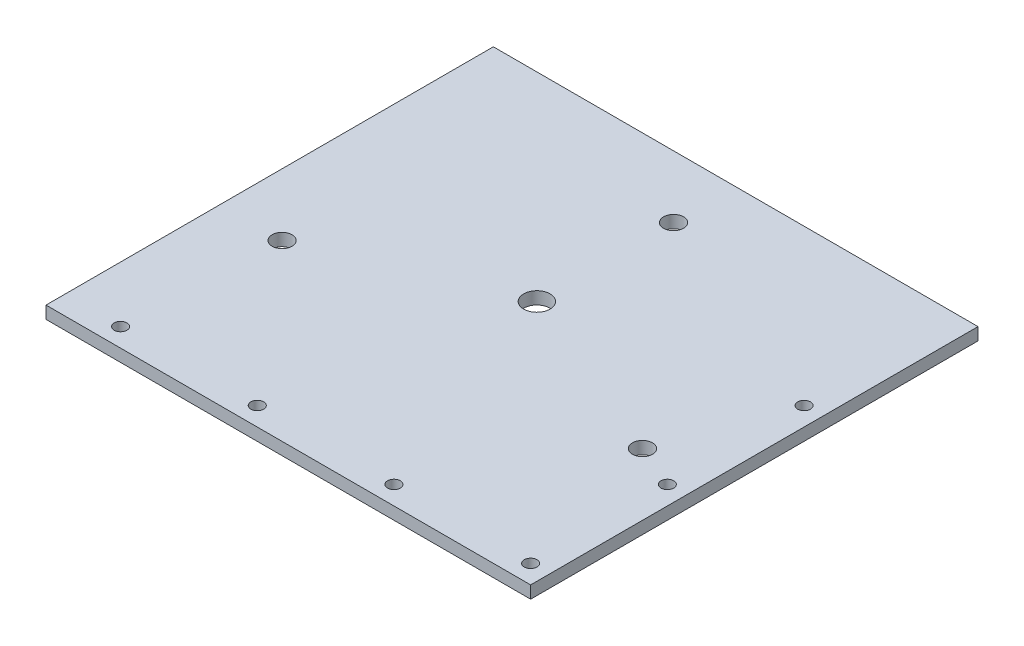
SolidWorks part; units mm, degrees
material "6061 Alloy"
ref_plane "Front Plane" through (0, 0, 0) normal (0, 0, 1) x (1, 0, 0)
ref_plane "Top Plane" through (0, 0, 0) normal (0, 1, 0) x (1, 0, 0)
ref_plane "Right Plane" through (0, 0, 0) normal (1, 0, 0) x (0, 0, -1)
sketch "Sketch1" plane through (0, 0, 0) normal (0, 1, 0) x (1, 0, 0)
  line L1 (-61.9125, -57.15) -> (61.9125, -57.15)
  line L2 (-61.9125, -57.15) -> (-61.9125, 57.15)
  line L3 (-61.9125, 57.15) -> (61.9125, 57.15)
  line L4 (61.9125, -57.15) -> (61.9125, 57.15)
  line L5 (-61.9125, -57.15) -> (61.9125, 57.15) construction
  line L6 (-61.9125, 57.15) -> (61.9125, -57.15) construction
  point P0 (0, 0)
  dimension "D1" = 114.3
  dimension "D2" = 123.825
extrude "Plate" add sketch "Sketch1" along normal blind 3.175 contours L1 L4 L3 L2
hole_wizard "Force Plate Post (1/4\"-20 Clearance Hole)" positions "Sketch21" profile "Sketch20" hole size "1/4" standard "ANSI Inch" end condition up to next
sketch "Sketch21" plane through (0, 3.175, 0) normal (0, 1, 0) x (1, 0, 0)
  point P0 (0, 6.35)
  dimension "D1" = 6.35
sketch "Sketch20" plane through (0, 3.175, -6.35) normal (1, 0, 0) x (0, 0, 1)
  line L0 (0, 0) -> (0, 3.175)
  line L1 (0, 3.175) -> (3.3782, 3.175)
  line L2 (3.3782, 3.175) -> (3.3782, 0)
  line L5 (3.3782, 0) -> (0, 0)
  line L11 (0, -6.35) -> (0, 107.95) construction
  dimension "Thru Hole Dia." = 6.7564
  dimension "Thru Hole Depth" = 3.175
hole_wizard "#4 Clearance Hole1" positions "Sketch23" profile "Sketch22" hole size "#4" standard "ANSI Inch" end condition up to next
sketch "Sketch23" plane through (0, 3.175, 0) normal (0, 1, 0) x (1, 0, 0)
  line L0 (57.15, -57.15) -> (57.15, 57.15) construction
  line L1 (-61.9125, -57.15) -> (61.9125, -57.15) construction
  line L2 (-61.9125, 57.15) -> (61.9125, 57.15) construction
  line L4 (-61.9125, -52.3875) -> (61.9125, -52.3875) construction
  line L5 (-61.9125, -57.15) -> (-61.9125, 57.15) construction
  line L6 (61.9125, -57.15) -> (61.9125, 57.15) construction
  point P17 (57.15, -52.3875)
  point P19 (57.15, -17.4625)
  point P21 (57.15, 17.4625)
  point P25 (22.225, -52.3875)
  point P27 (-12.7, -52.3875)
  point P35 (-47.625, -52.3875)
  dimension "D1" = 4.7625
  dimension "D2" = 4.7625
  dimension "D3" = 34.925
  dimension "D4" = 34.925
  dimension "D5" = 34.925
  dimension "D6" = 34.925
  dimension "D7" = 34.925
sketch "Sketch22" plane through (57.15, 3.175, 52.3875) normal (1, 0, 0) x (0, 0, 1)
  line L0 (0, 0) -> (0, 3.175)
  line L1 (0, 3.175) -> (1.6319, 3.175)
  line L2 (1.6319, 3.175) -> (1.6319, 0)
  line L5 (1.6319, 0) -> (0, 0)
  line L11 (0, -6.35) -> (0, 107.95) construction
  dimension "Thru Hole Dia." = 3.2639
  dimension "Thru Hole Depth" = 3.175
hole_wizard "#10 Clearance Hole1" positions "Sketch25" profile "Sketch24" hole size "#10" standard "ANSI Inch" end condition up to next
sketch "Sketch25" plane through (0, 3.175, 0) normal (0, 1, 0) x (1, 0, 0)
  line L0 (-61.9125, 57.15) -> (61.9125, 57.15) construction
  line L1 (-61.9125, -57.15) -> (-61.9125, 57.15) construction
  line L2 (-61.9125, -57.15) -> (61.9125, -57.15) construction
  line L3 (61.9125, -57.15) -> (61.9125, 57.15) construction
  point P0 (0, 41.275)
  point P4 (-46.0375, -12.7)
  point P6 (46.0375, -12.7)
  dimension "D1" = 15.875
  dimension "D2" = 15.875
  dimension "D3" = 44.45
  dimension "D4" = 15.875
sketch "Sketch24" plane through (0, 3.175, -41.275) normal (1, 0, 0) x (0, 0, 1)
  line L0 (0, 0) -> (0, 3.175)
  line L1 (0, 3.175) -> (2.5527, 3.175)
  line L2 (2.5527, 3.175) -> (2.5527, 0)
  line L5 (2.5527, 0) -> (0, 0)
  line L11 (0, -6.35) -> (0, 107.95) construction
  dimension "Thru Hole Dia." = 5.1054
  dimension "Thru Hole Depth" = 3.175
